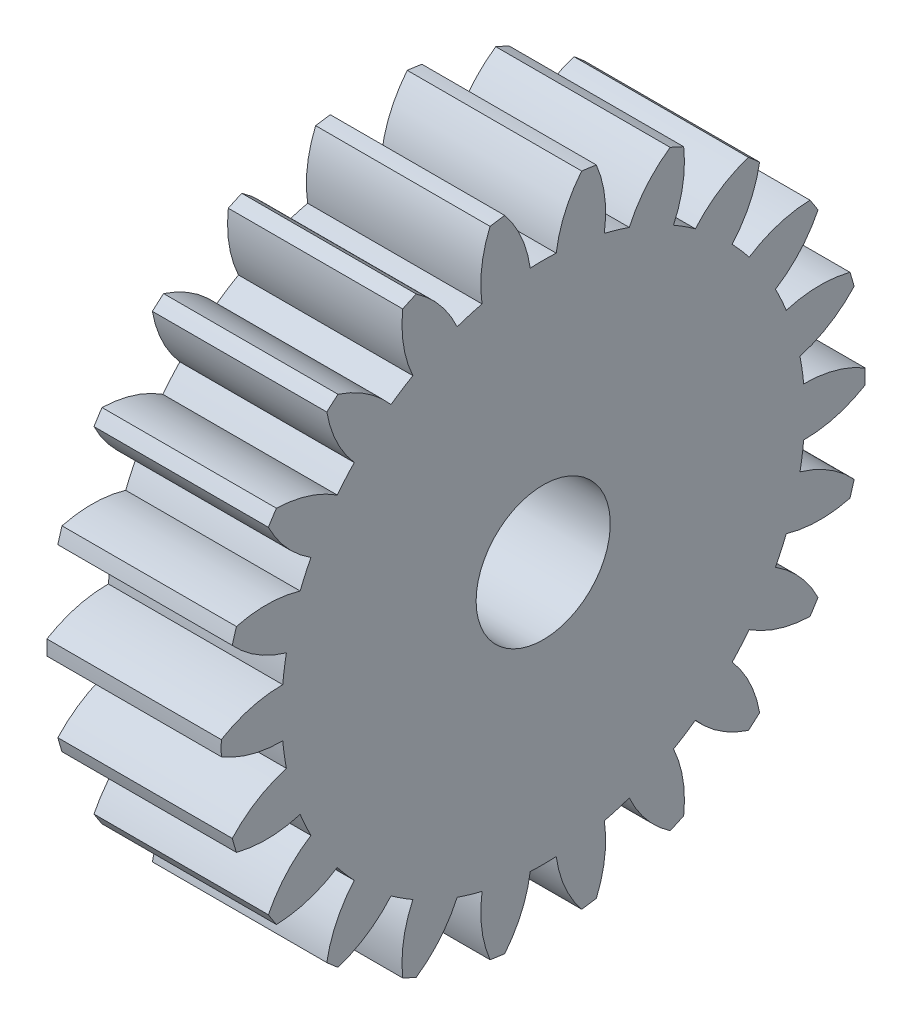
SolidWorks part; units mm, degrees
ref_plane "Plane1" through (0, 0, 0) normal (0, 0, 1) x (1, 0, 0)
ref_plane "Plane2" through (0, 0, 0) normal (0, 1, 0) x (1, 0, 0)
ref_plane "Plane3" through (0, 0, 0) normal (1, 0, 0) x (0, 0, -1)
other "Configuration Table"
sketch "HoldingSke" plane through (0, 0, 0) normal (0, 1, 0) x (1, 0, 0)
  line L0 (0, 0) -> (0.4636, -0.1873)
  line L1 (-15, 0) -> (100, 0) construction
  line L2 (0, 0) -> (-2.1039, 2.3779)
  line L3 (0, 0) -> (-11.863, 4.5341)
  line L4 (0, 0) -> (8.0072, 3.2351)
  line L5 (0, 0) -> (-15.9282, -5.9407)
  line L6 (0, 0) -> (-10.7765, -7.2709)
  line L7 (-2.1039, 2.3779) -> (1.5554, 18.9794)
  line L8 (-76.2, 54.61) -> (-74.4, 54.61)
  line L9 (-71.009, 38.7566) -> (-53.1078, 45.2721)
  line L10 (-76.2, 71.12) -> (104.1128, 71.12)
  line L11 (0, 0) -> (-13, 0)
  line L12 (-76.2, 101.6) -> (-76.133, 101.6)
  line L13 (24.9733, 27.94) -> (52.9518, 28.4284)
  line L14 (24.9733, 27.94) -> (24.9743, 27.94)
  line L15 (24.9733, 27.94) -> (100.4006, 29.5858)
  line L16 (-63.627, -2) -> (-12.827, -2)
  circle A0 centre (0, 0) radius 5
  circle A1 centre (0, 0) radius 6
  circle A2 centre (0, 0) radius 6
  circle A3 centre (0, 0) radius 5
  dimension "MHD" = 12
  dimension "Hub_dia" = 12
  dimension "Bore" = 10
  dimension "MBD" = 10
  dimension "Num_teeth" = 22
  dimension "Pitch" = 0.5
  dimension "Overall_len" = 17
  dimension "Show_teeth" = 22
  dimension "Thickness" = 13
  dimension "OAL" = 17.0001
  dimension "T_dim" = 1.8
  dimension "Ap" = 20
  dimension "H" = 19.05
  dimension "Pitch_radius" = 180.3128
  dimension "Width" = 13
  dimension "Backlash" = 0.067
  dimension "Addendum_fac" = 1
  dimension "Dedendum_fac" = 1.25
  dimension "Clearance_fac" = 0.25
  dimension "Dedendum_add" = 0.001
  dimension "Module" = 2
sketch "BasProSke" plane through (0, 0, 0) normal (0, 1, 0) x (1, 0, 0)
  line L0 (-10, 0) -> (60, 0) construction
  line L1 (0, 0) -> (0, 24)
  line L2 (0, 0) -> (13, 0)
  line L3 (13, 0) -> (13, 24)
  line L4 (13, 24) -> (0, 24)
  dimension "Thickness" = 13
  dimension "Diameter" = 48
revolve "Base-Revolve" add sketch "BasProSke" angle 360 about L0
sketch "TooCutSke" plane through (0, 0, 0) normal (1, 0, 0) x (0, 0, -1)
  line L1 (0, 0) -> (0, 107) construction
  line L2 (0, 0) -> (-1.6867, 21.9352) construction
  line L3 (0, 0) -> (-6.2482, 43.4572) construction
  line L4 (-1.6867, 21.9352) -> (-3.1241, 21.7286) construction
  arc A0 (0.9682, 19.4749) -> (-0.9682, 19.4749) centre (0, 0) ccw
  arc A1 (2.8856, 23.8515) -> (-2.8856, 23.8515) centre (0, 0) ccw
  circle A2 centre (0, 0) radius 22 construction
  circle A3 centre (0, 0) radius 20.6732 construction
  arc A4 (-0.9682, 19.4749) -> (-2.8856, 23.8515) centre (-9.6845, 18.2645) ccw
  arc A5 (2.8856, 23.8515) -> (0.9682, 19.4749) centre (9.6845, 18.2645) ccw
  dimension "Root_dia" = 38.998
  dimension "Overcut_dia" = 48.0508
  dimension "Pitch_dia" = 44
  dimension "Base_dia" = 41.3465
  dimension "Flank_rad" = 8.8
  dimension "Half_ang" = 8.182
  dimension "Half_CT" = 1.4522
extrude "ToothCut" cut sketch "TooCutSke" along normal through all
fillet "Breaks" [suppressed] radius 0.04
fillet "RootFillets" [suppressed] radius 0.501
pattern_circular "TeethCuts" count 22 every 16.364 about axis through (-10, 0, 0) along (1, 0, 0) of "ToothCut", "RootFillets", "Breaks"
sketch "HubNeaOneSke" plane through (0, 0, 0) normal (-1, 0, 0) x (0, 0, 1)
  circle A0 centre (0, 0) radius 6
  dimension "Diameter" = 12
extrude "HubNearOne" add sketch "HubNeaOneSke" along normal blind 4.0001
sketch "HubNeaBotSke" plane through (0, 0, 0) normal (-1, 0, 0) x (0, 0, 1)
  circle A0 centre (0, 0) radius 6
  dimension "Diameter" = 12
extrude "HubNearBoth" [suppressed] add sketch "HubNeaBotSke" along normal blind 2
ref_plane "FarPln" through (13, 0, 0) normal (1, 0, 0) x (0, 0, -1)
sketch "HubFarSke" plane through (13, 0, 0) normal (1, 0, 0) x (0, 0, -1)
  circle A0 centre (0, 0) radius 6
  dimension "Diameter" = 12
extrude "HubFar" [suppressed] add sketch "HubFarSke" along normal blind 2
sketch "BorSke" plane through (0, 0, 0) normal (1, 0, 0) x (0, 0, -1)
  circle A0 centre (0, 0) radius 5
  dimension "Diameter" = 10
extrude "Bore" cut sketch "BorSke" along normal mid plane 34.0001
sketch "KeySke" plane through (0, 0, 0) normal (1, 0, 0) x (0, 0, -1)
  line L0 (-2, 0) -> (-2, 6.8)
  line L1 (-2, 6.8) -> (2, 6.8)
  line L2 (2, 6.8) -> (2, 0)
  line L3 (0, 0) -> (0, 34) construction
  line L4 (-2, 0) -> (2, 0)
  dimension "Offset" = 6.8
  dimension "Width" = 4
extrude "Keyway" [suppressed] cut sketch "KeySke" along normal mid plane 34.0001
pattern_circular "Keyway2" [suppressed] count 2 every 90 about axis through (-10, 0, 0) along (1, 0, 0)
scale "Scale1" scale about centroid uniform scaling yes scale factor 0.317565
equation "' \"Module@HoldingSke\" = 6.35"
equation "' \"Num_teeth@HoldingSke\" = 12"
equation "' \"Ap@HoldingSke\" =  20"
equation "' \"Ap@HoldingSke\" = 20"
equation "' \"Width@HoldingSke\" = 0.5 * 25.4"
equation "' \"Hub_dia@HoldingSke\"= 1 * 25.4"
equation "' \"Hub_dia@HoldingSke\" = 1 * 25.4"
equation "' \"Overall_len@HoldingSke\" = 1.0 * 25.4"
equation "' \"Bore@HoldingSke\" = 0.75 * 25.4"
equation "' \"T_dim@HoldingSke\" = 0.1 * 25.4"
equation "' \"Width@KeySke\" = 0.25 * 25.4"
equation "' \"Show_teeth@HoldingSke\" = 13"
equation "' \"Backlash@HoldingSke\" = 0.009 * 25.4"
equation "' \"Addendum_fac@HoldingSke\" = 1.0"
equation "' \"Dedendum_fac@HoldingSke\" = 1.25"
equation "' \"Dedendum_add@HoldingSke\" = 0.00005 * 25.4"
equation "' \"Clearance_fac@HoldingSke\" = 0.25"
equation "\"Pitch@HoldingSke\" = 1 / \"Module@HoldingSke\""
equation "\"Overcut_dia@TooCutSke\" = (\"Num_teeth@HoldingSke\" + 2 * \"Addendum_fac@HoldingSke\") / \"Pitch@HoldingSke\" + 0.002 * 25.4"
equation "\"Pitch_dia@TooCutSke\" = \"Num_teeth@HoldingSke\" / \"Pitch@HoldingSke\""
equation "\"Base_dia@TooCutSke\" = \"Num_teeth@HoldingSke\" / \"Pitch@HoldingSke\" * cos((\"Ap@HoldingSke\"  * 3.14159265 / 180))"
equation "\"Root_dia@TooCutSke\" = (\"Num_teeth@HoldingSke\" + 2) / \"Pitch@HoldingSke\" - 2 * (\"Addendum_fac@HoldingSke\" + \"Dedendum_fac@HoldingSke\") / \"Pitch@HoldingSke\" - \"Dedendum_add@HoldingSke\" * 2"
equation "\"Half_ang@TooCutSke\" = 180 / \"Num_teeth@HoldingSke\""
equation "\"Half_CT@TooCutSke\" = \"Num_teeth@HoldingSke\" / \"Pitch@HoldingSke\" * sin((3.14159265 / 2 / \"Num_teeth@HoldingSke\")) / 2 - 7 * \"Backlash@HoldingSke\" / 4"
equation "\"Flank_rad@TooCutSke\" = \"Num_teeth@HoldingSke\" / \"Pitch@HoldingSke\" / 5"
equation "\"Radius@RootFillets\" = \"Clearance_fac@HoldingSke\" / \"Pitch@HoldingSke\" + \"Dedendum_add@HoldingSke\""
equation "\"Break_rad@Breaks\" = 0.02 / \"Pitch@HoldingSke\""
equation "\"Thickness@HoldingSke\" = \"Width@HoldingSke\""
equation "\"OAL@HoldingSke\" = \"Thickness@HoldingSke\""
equation "\"MHD@HoldingSke\" = (\"Num_teeth@HoldingSke\" + 2) / \"Pitch@HoldingSke\" - 2 * (\"Addendum_fac@HoldingSke\" + \"Dedendum_fac@HoldingSke\")  / \"Pitch@HoldingSke\" - \"Dedendum_add@HoldingSke\" * 2"
equation "\"MBD@HoldingSke\" = (\"Num_teeth@HoldingSke\" + 2) / \"Pitch@HoldingSke\" - 2 * (\"Addendum_fac@HoldingSke\" + \"Dedendum_fac@HoldingSke\")  / \"Pitch@HoldingSke\" - \"Dedendum_add@HoldingSke\" * 2 - 0.002 * 25.4"
equation "\"MHD@HoldingSke\" = ((sgn( \"MHD@HoldingSke\" - \"Hub_dia@HoldingSke\" )-1)*( \"MHD@HoldingSke\" - \"Hub_dia@HoldingSke\" ))/-2+ \"Hub_dia@HoldingSke\""
equation "\"MBD@HoldingSke\" = ((sgn( \"MBD@HoldingSke\" - \"Bore@HoldingSke\" )-1)*( \"MBD@HoldingSke\" - \"Bore@HoldingSke\" ))/-2+ \"Bore@HoldingSke\""
equation "\"OAL@HoldingSke\" = ((sgn( \"OAL@HoldingSke\" - \"Overall_len@HoldingSke\" )+1)*( \"OAL@HoldingSke\" - \"Overall_len@HoldingSke\" ))/2 + \"Overall_len@HoldingSke\" + 0.000002 * 25.4"
equation "\"Num_teeth@TeethCuts\" = int( \"Show_teeth@HoldingSke\" ) + 1"
equation "\"Num_teeth@TeethCuts\" = ((sgn( \"Num_teeth@TeethCuts\" - \"Num_teeth@HoldingSke\" )-1)*( \"Num_teeth@TeethCuts\" - \"Num_teeth@HoldingSke\" ))/-2+ \"Num_teeth@HoldingSke\""
equation "\"Num_teeth@TeethCuts\" = ((sgn( \"Num_teeth@TeethCuts\" - 2.0)+1)*( \"Num_teeth@TeethCuts\" - 2.0))/2 +2.0"
equation "\"Angle@TeethCuts\" = 360.0 / \"Num_teeth@HoldingSke\""
equation "\"Diameter@BasProSke\" = (\"Num_teeth@HoldingSke\" + 2 * \"Addendum_fac@HoldingSke\") / \"Pitch@HoldingSke\""
equation "\"Thickness@BasProSke\"  = \"Thickness@HoldingSke\""
equation "' \"Fillet_rad@BasProSke\" =  \"Thickness@HoldingSke\" * 0.05"
equation "' \"Fillet_rad@BasProSke\" = \"Thickness@HoldingSke\" * 0.05"
equation "\"MHD@HoldingSke\" = ((sgn( \"MHD@HoldingSke\" - \"Root_dia@TooCutSke\" )-1)*( \"MHD@HoldingSke\" - \"Root_dia@TooCutSke\" ))/-2+ \"Root_dia@TooCutSke\""
equation "\"Diameter@HubNeaOneSke\" = \"MHD@HoldingSke\""
equation "\"Length@HubNearOne\" = \"OAL@HoldingSke\" - \"Thickness@BasProSke\""
equation "\"Diameter@HubNeaBotSke\" = \"MHD@HoldingSke\""
equation "\"Length@HubNearBoth\" = ( \"OAL@HoldingSke\" - \"Thickness@BasProSke\" ) / 2.0"
equation "\"Thickness@FarPln\" = \"Thickness@BasProSke\""
equation "\"Diameter@HubFarSke\" = \"MHD@HoldingSke\""
equation "\"Length@HubFar\" = ( \"OAL@HoldingSke\" - \"Thickness@BasProSke\" ) / 2.0"
equation "\"Diameter@BorSke\" = \"MBD@HoldingSke\""
equation "\"D1@Bore\" = \"OAL@HoldingSke\" * 2.0"
equation "\"D1@Keyway\" = \"OAL@HoldingSke\" * 2.0"
equation "\"Offset@KeySke\" = \"T_dim@HoldingSke\" + \"MBD@HoldingSke\" / 2.0"
